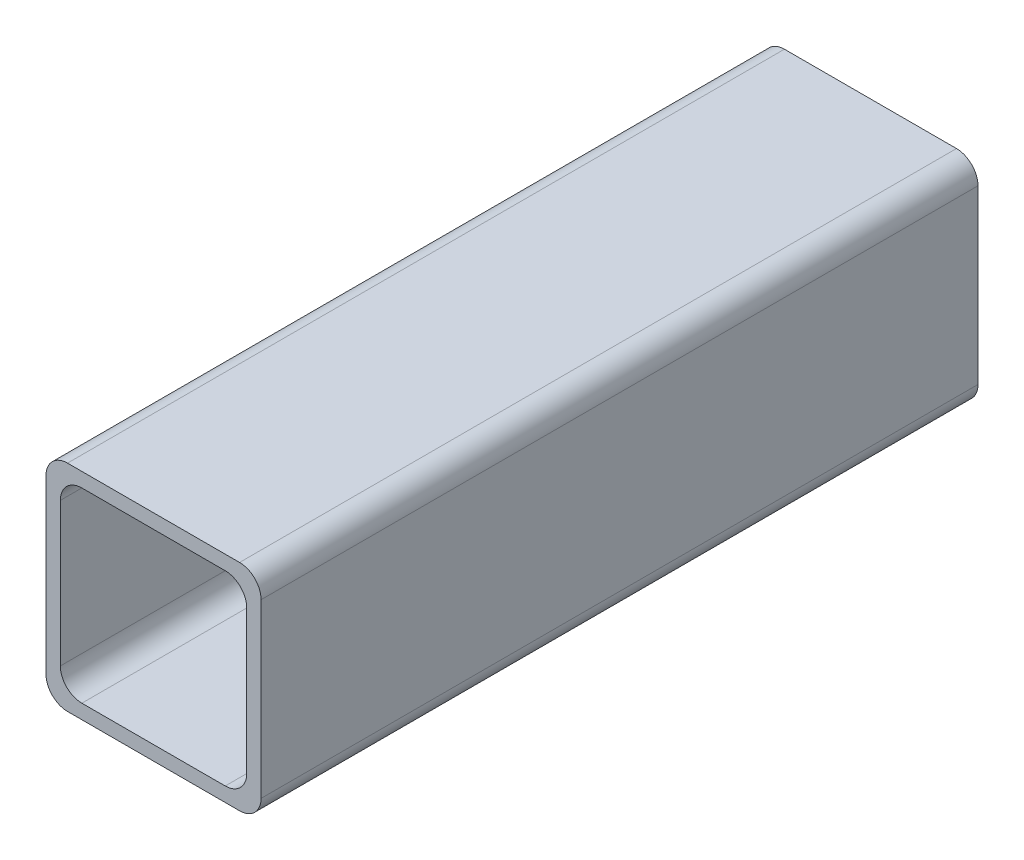
SolidWorks part; units mm, degrees
ref_plane "Plan de face" through (0, 0, 0) normal (0, 0, 1) x (1, 0, 0)
ref_plane "Plan de dessus" through (0, 0, 0) normal (0, 1, 0) x (1, 0, 0)
ref_plane "Plan de droite" through (0, 0, 0) normal (1, 0, 0) x (0, 0, -1)
sketch "Esquisse1" plane through (0, 0, 0) normal (0, 0, 1) x (1, 0, 0)
  line L1 (-12, -15) -> (12, -15)
  line L2 (-15, -12) -> (-15, 12)
  line L3 (-12, 15) -> (12, 15)
  line L4 (15, -12) -> (15, 12)
  line L5 (0, 15) -> (0, -15) construction
  line L6 (-15, 0) -> (15, 0) construction
  line L7 (-10, -13) -> (10, -13)
  line L8 (-13, -10) -> (-13, 10)
  line L9 (-10, 13) -> (10, 13)
  line L10 (13, -10) -> (13, 10)
  line L11 (0, 13) -> (0, -13) construction
  line L12 (-13, 0) -> (13, 0) construction
  arc A0 (10, -13) -> (13, -10) centre (10, -10) ccw
  arc A1 (12, -15) -> (15, -12) centre (12, -12) ccw
  arc A2 (-13, 10) -> (-10, 13) centre (-10, 10) cw
  arc A3 (-10, -13) -> (-13, -10) centre (-10, -10) cw
  arc A4 (10, 13) -> (13, 10) centre (10, 10) cw
  arc A5 (-15, 12) -> (-12, 15) centre (-12, 12) cw
  arc A6 (-12, -15) -> (-15, -12) centre (-12, -12) cw
  arc A7 (12, 15) -> (15, 12) centre (12, 12) cw
  point P0 (0, 0)
  point P4 (0, 0)
  point P13 (13, -13)
  point P19 (15, -15)
  point P22 (-13, 13)
  point P25 (-13, -13)
  point P30 (-15, 15)
  point P33 (-15, -15)
  dimension "D5" = 3
  dimension "D1" = 30
  dimension "D2" = 26
  dimension "D3" = 30
  dimension "D4" = 26
extrude "Boss.-Extru.1" add sketch "Esquisse1" against normal blind 100
